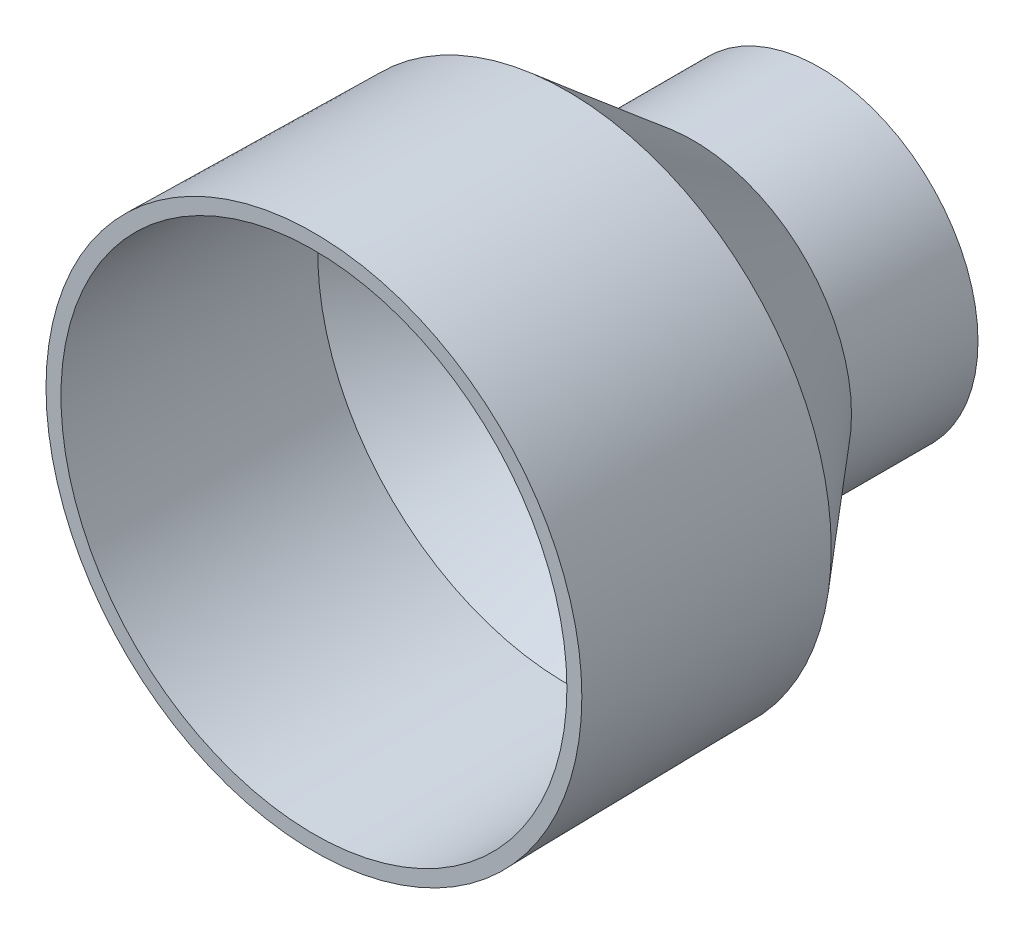
SolidWorks part; units mm, degrees
ref_plane "Front Plane" through (0, 0, 0) normal (0, 0, 1) x (1, 0, 0)
ref_plane "Top Plane" through (0, 0, 0) normal (0, 1, 0) x (1, 0, 0)
ref_plane "Right Plane" through (0, 0, 0) normal (1, 0, 0) x (0, 0, -1)
sketch "Sketch3" plane through (0, 0, 0) normal (1, 0, 0) x (0, 0, -1)
  line L0 (0, 50.8) -> (50.8, 50.038)
  line L2 (0.045, 53.7997) -> (50.845, 53.0377)
  line L4 (0, 0) -> (50000, 0) construction
  line L5 (101.6, 31.75) -> (76.2, 31.75)
  line L6 (101.6, 31.75) -> (101.6, 28.575)
  line L7 (101.6, 28.575) -> (76.2, 28.575)
  line L8 (76.2, 31.75) -> (76.2, 28.575) construction
  line L9 (0, 50.8) -> (0, 53.8003)
  line L10 (0, 53.8003) -> (0.045, 53.7997)
  line L11 (76.2, 28.575) -> (50.8, 50.038)
  line L12 (76.2, 31.75) -> (50.845, 53.0377)
  point P11 (0, 0)
  dimension "D1" = 50.8
  dimension "D2" = 50.038
  dimension "D3" = 50.8
  dimension "D5" = 28.575
  dimension "D6" = 31.75
  dimension "D7" = 101.6
  dimension "D8" = 25.4
  dimension "D4" = 3
revolve "Revolve1" add sketch "Sketch3" angle 360 about L4
